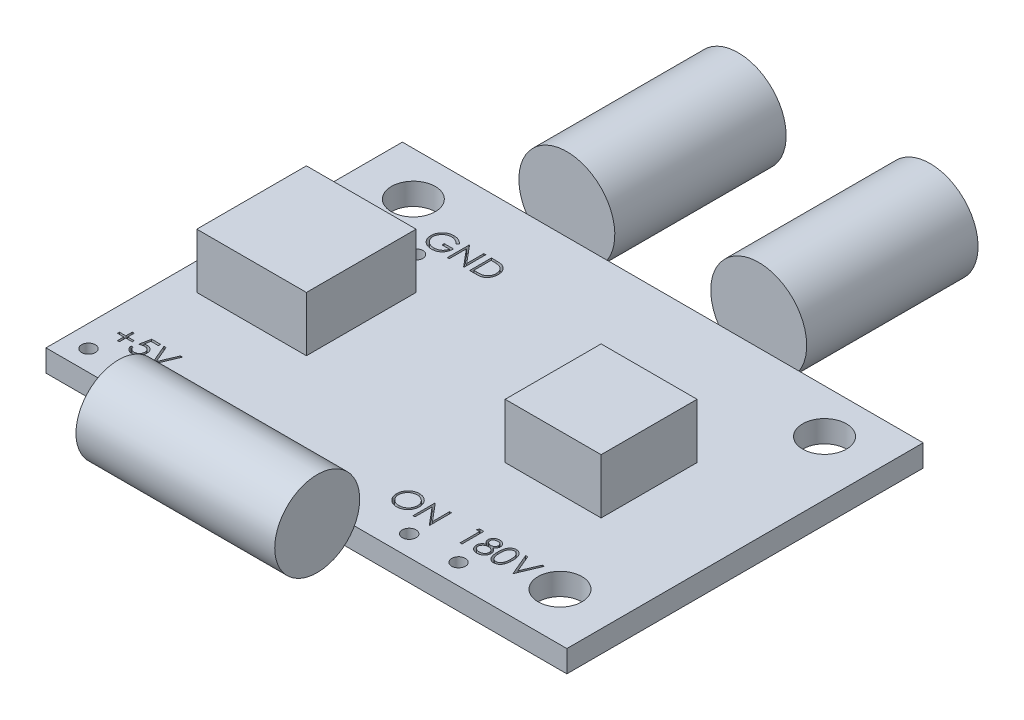
SolidWorks part; units mm, degrees
ref_plane "Front Plane" through (0, 0, 0) normal (0, 0, 1) x (1, 0, 0)
ref_plane "Top Plane" through (0, 0, 0) normal (0, 1, 0) x (1, 0, 0)
ref_plane "Right Plane" through (0, 0, 0) normal (1, 0, 0) x (0, 0, -1)
sketch "Sketch1" plane through (0, 0, 0) normal (0, 1, 0) x (1, 0, 0)
  line L1 (0, 0) -> (38, 0)
  line L2 (0, 0) -> (0, 26)
  line L3 (0, 26) -> (38, 26)
  line L4 (38, 0) -> (38, 26)
  circle A0 centre (28.6, 1.5) radius 0.5
  circle A1 centre (25, 1.5) radius 0.5
  circle A2 centre (1.6, 1.5) radius 0.5
  circle A3 centre (7.6, 19.4) radius 0.5
  circle A4 centre (4, 22.8) radius 1.6
  circle A5 centre (34, 22.8) radius 1.6
  circle A6 centre (34, 3.5) radius 1.6
  dimension "D9" = 1
  dimension "D10" = 3.2
  dimension "D1" = 38
  dimension "D2" = 26
  dimension "D3" = 1.5
  dimension "D4" = 19.4
  dimension "D5" = 9.4
  dimension "D6" = 13
  dimension "D7" = 36.4
  dimension "D8" = 30.4
  dimension "D11" = 4
  dimension "D12" = 3.5
  dimension "D13" = 22.8
  dimension "D14" = 4
extrude "Boss-Extrude1" add sketch "Sketch1" along normal blind 1.6
sketch "Sketch2" plane through (0, 1.6, 0) normal (0, 1, 0) x (1, 0, 0)
  line L0 (0, 26) -> (0, 0) construction
  line L1 (2, 17) -> (10, 17)
  line L2 (2, 17) -> (2, 9)
  line L3 (2, 9) -> (10, 9)
  line L4 (10, 17) -> (10, 9)
  line L5 (38, 0) -> (38, 26) construction
  line L6 (24, 16.5) -> (31, 16.5)
  line L7 (24, 16.5) -> (24, 9.5)
  line L8 (24, 9.5) -> (31, 9.5)
  line L9 (31, 16.5) -> (31, 9.5)
  point P6 (0, 13)
  point P7 (2, 13)
  point P14 (38, 13)
  point P15 (31, 13)
  dimension "D1" = 8
  dimension "D2" = 10
  dimension "D3" = 7
  dimension "D4" = 14
extrude "Boss-Extrude2" add sketch "Sketch2" along normal blind 4
sketch "Sketch3" plane through (0, 0, 0) normal (-1, 0, 0) x (0, 0, 1)
  line L0 (-26, 0) -> (0, 0) construction
  circle A0 centre (2.7129, 3.1) radius 3.1
  dimension "D1" = 6.2
extrude "Boss-Extrude3" add sketch "Sketch3" against normal blind 14.5 from offset 8 separate body offset against normal yes
sketch "Sketch4" plane through (0, 0, -26) normal (0, 0, -1) x (-1, 0, 0)
  line L0 (-38, 0) -> (0, 0) construction
  line L1 (-38, 1.6) -> (-38, 0) construction
  line L2 (0, 1.6) -> (0, 0) construction
  circle A0 centre (-26, 3.5) radius 3.5
  circle A1 centre (-12, 3.5) radius 3.5
  dimension "D1" = 7
  dimension "D2" = 12
  dimension "D3" = 12
extrude "Boss-Extrude4" add sketch "Sketch4" along normal blind 12.5
sketch "Sketch5" plane through (0, 1.6, 0) normal (0, 1, 0) x (1, 0, 0)
  text T0 "ON" font "Century Gothic" height in points 6
  text T1 "180V" font "Century Gothic" height in points 6
  text T2 "GND" font "Century Gothic" height in points 6
  text T3 "+5V" font "Century Gothic" height in points 6
extrude "Cut-Extrude1" cut sketch "Sketch5" against normal blind 0.5
